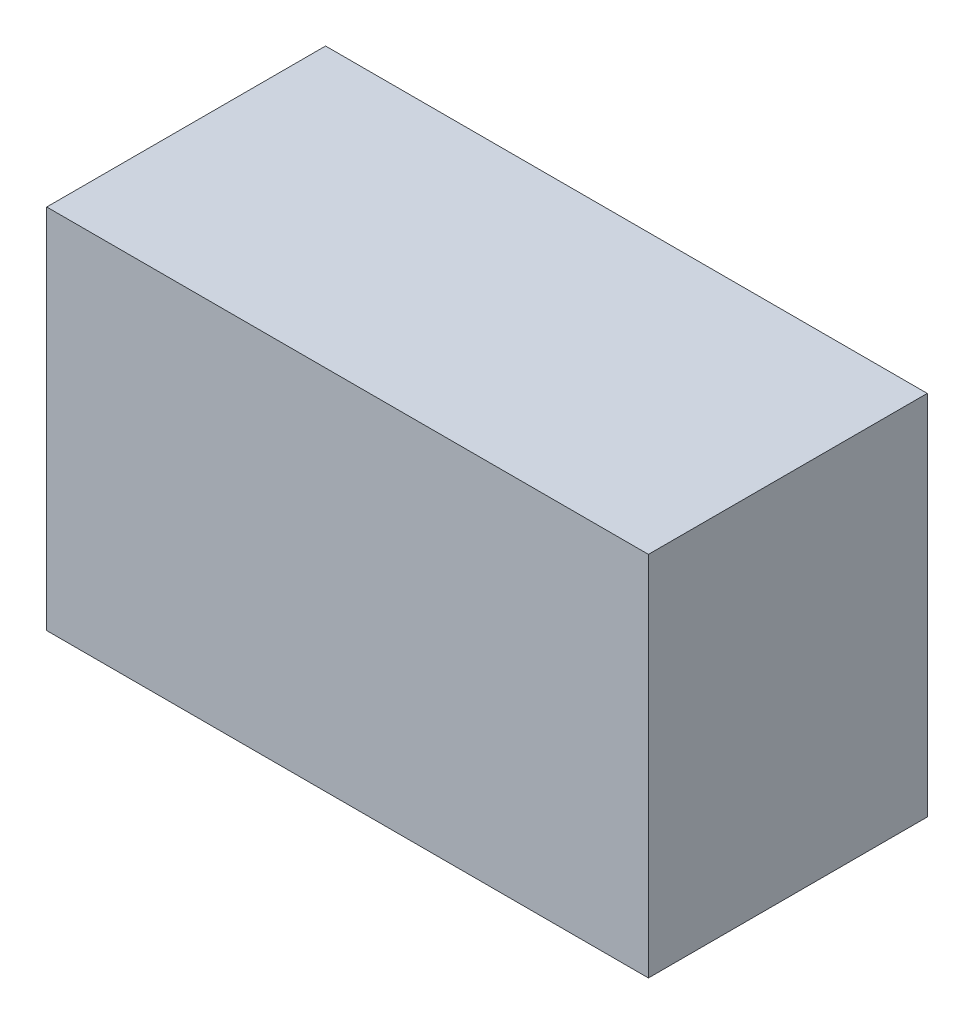
SolidWorks part; units mm, degrees
material "ABS"
ref_plane "前视基准面" through (0, 0, 0) normal (0, 0, 1) x (1, 0, 0)
ref_plane "上视基准面" through (0, 0, 0) normal (0, 1, 0) x (1, 0, 0)
ref_plane "右视基准面" through (0, 0, 0) normal (1, 0, 0) x (0, 0, -1)
sketch "草图2" plane through (0, 0, 0) normal (0, 0, 1) x (1, 0, 0)
  line L1 (-20.5, 12.5) -> (20.5, 12.5)
  line L2 (-20.5, 12.5) -> (-20.5, -12.5)
  line L3 (-20.5, -12.5) -> (20.5, -12.5)
  line L4 (20.5, 12.5) -> (20.5, -12.5)
  line L5 (-20.5, 12.5) -> (20.5, -12.5) construction
  line L6 (-20.5, -12.5) -> (20.5, 12.5) construction
  point P0 (0, 0)
  dimension "D1" = 41
  dimension "D2" = 25
extrude "凸台-拉伸1" add sketch "草图2" along normal blind 19
